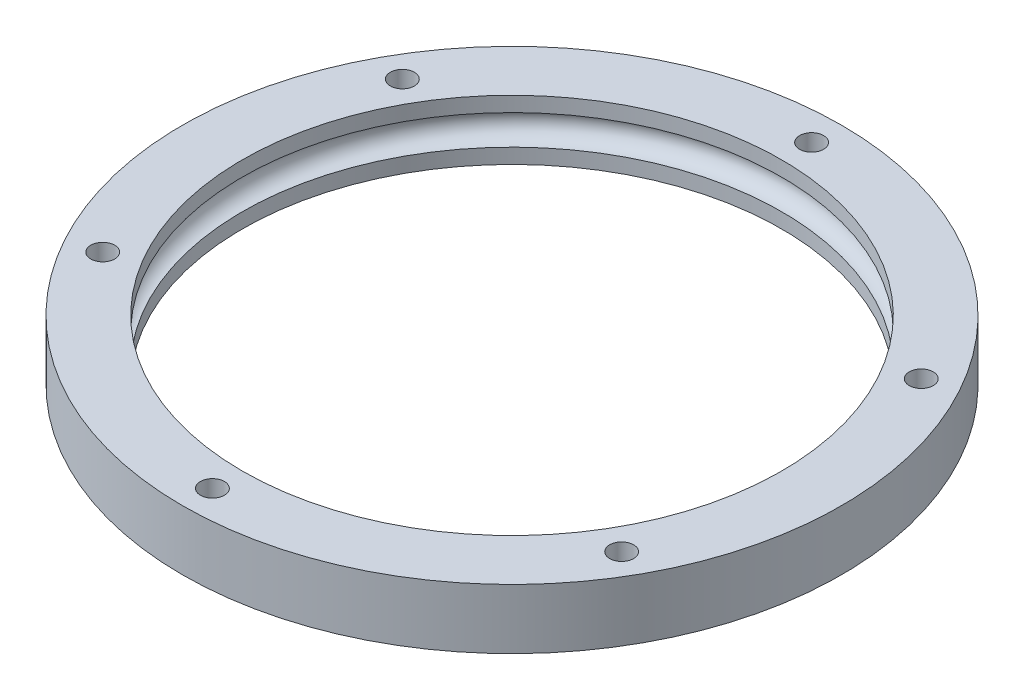
SolidWorks part; units mm, degrees
ref_plane "Alzado" through (0, 0, 0) normal (0, 0, 1) x (1, 0, 0)
ref_plane "Planta" through (0, 0, 0) normal (0, 1, 0) x (1, 0, 0)
ref_plane "Vista lateral" through (0, 0, 0) normal (1, 0, 0) x (0, 0, -1)
sketch "Croquis1" plane through (0, 0, 0) normal (1, 0, 0) x (0, 0, -1)
  line L0 (0, 59.0708) -> (0, -40.8641) construction
  line L1 (-45, 2.5) -> (-45, 5)
  line L2 (-45, -5) -> (-55, -5)
  line L3 (-45, -5) -> (-45, -2.5)
  line L4 (-45, 5) -> (-55, 5)
  line L5 (-55, -5) -> (-55, 5)
  line L6 (-45, -5) -> (-55, 5) construction
  line L7 (-45, 5) -> (-55, -5) construction
  arc A0 (-45, 2.5) -> (-45, -2.5) centre (-45, 0) ccw
  point P3 (-50, 0)
  dimension "D2" = 5
  dimension "D1" = 10
  dimension "D3" = 45
  dimension "D4" = 10
revolve "Revolución1" add sketch "Croquis1" angle 360 about L0
sketch "Croquis2" plane through (0, 5, 0) normal (0, 1, 0) x (1, 0, 0)
  line L0 (0, 0) -> (0, 57.948) construction
  circle A0 centre (0, 50) radius 2
  circle A1 centre (0, 0) radius 13.1613 construction
  circle A2 centre (43.3013, 25) radius 2
  circle A3 centre (43.3013, -25) radius 2
  circle A4 centre (0, -50) radius 2
  circle A5 centre (-43.3013, -25) radius 2
  circle A6 centre (-43.3013, 25) radius 2
  point P18 (0, 0)
  dimension "D1" = 4
  dimension "D3" = 6
  dimension "D2" = 50
extrude "Cortar-Extruir1" cut sketch "Croquis2" against normal blind 10
